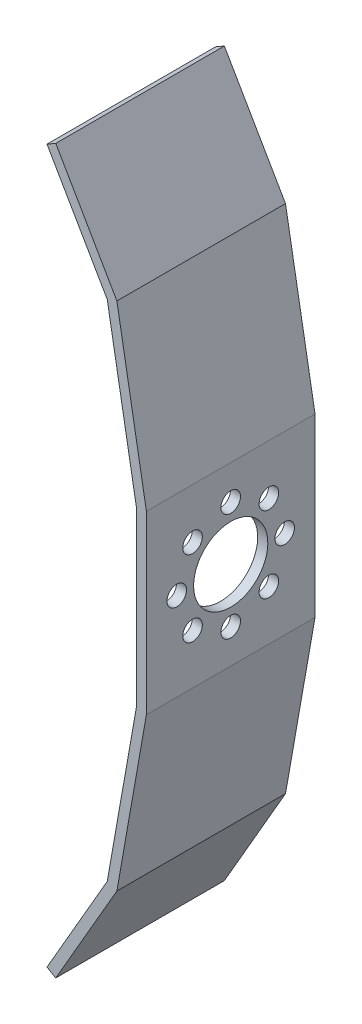
SolidWorks part; units mm, degrees
ref_plane "前视基准面" through (0, 0, 0) normal (0, 0, 1) x (1, 0, 0)
ref_plane "上视基准面" through (0, 0, 0) normal (0, 1, 0) x (1, 0, 0)
ref_plane "右视基准面" through (0, 0, 0) normal (1, 0, 0) x (0, 0, -1)
sketch "草图1" plane through (0, 0, 0) normal (0, 0, 1) x (1, 0, 0)
  line L0 (-13.3412, 53.2087) -> (-4.3412, 37.6202)
  line L1 (-4.3412, 37.6202) -> (0, 13)
  line L2 (0, 13) -> (0, -13)
  line L3 (0, -13) -> (-4.3412, -37.6202)
  line L4 (-4.3412, -37.6202) -> (-13.3412, -53.2087)
  dimension "D1" = 13
  dimension "D2" = 26
  dimension "D3" = 25
  dimension "D4" = 18
  dimension "D5" = 170
  dimension "D6" = 160
  dimension "D7" = 170
  dimension "D8" = 160
extrude "拉伸-薄壁1" add sketch "草图1" along normal blind 25 thin thin type mid plane wall 1.5
sketch "草图2" plane through (0.75, 0, 0) normal (1, 0, 0) x (0, 0, -1)
  line L0 (-25, 13.0656) -> (0, 13.0656) construction
  circle A0 centre (-12.5, 0) radius 5.5
  circle A2 centre (-20.5, 0) radius 1.45
  circle A5 centre (-18.1569, 5.6569) radius 1.45
  circle A6 centre (-12.5, 8) radius 1.45
  circle A7 centre (-6.8431, 5.6569) radius 1.45
  circle A8 centre (-4.5, 0) radius 1.45
  circle A9 centre (-6.8431, -5.6569) radius 1.45
  circle A10 centre (-12.5, -8) radius 1.45
  circle A11 centre (-18.1569, -5.6569) radius 1.45
  point P6 (-12.5, 13.0656)
  point P17 (-12.5, 0)
  dimension "D2" = 11
  dimension "D3" = 2.9
  dimension "D1" = 8
  dimension "D4" = 8
extrude "切除-拉伸1" cut sketch "草图2" against normal blind 10
